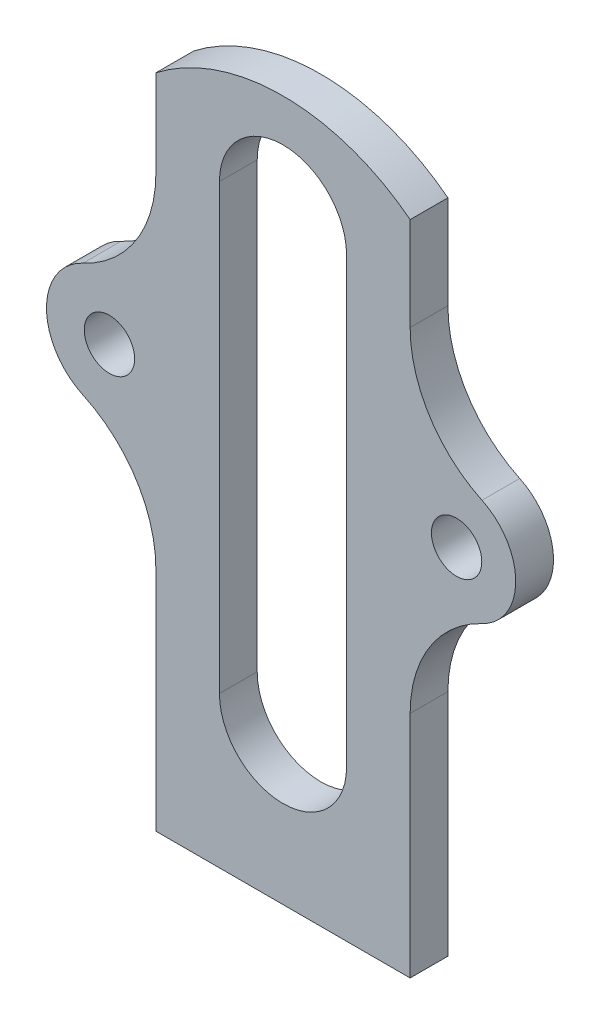
SolidWorks part; units mm, degrees
ref_plane "Front Plane" through (0, 0, 0) normal (0, 0, 1) x (1, 0, 0)
ref_plane "Top Plane" through (0, 0, 0) normal (0, 1, 0) x (1, 0, 0)
ref_plane "Right Plane" through (0, 0, 0) normal (1, 0, 0) x (0, 0, -1)
ref_plane "Plane1" through (0, 0, 26) normal (0, 0, 1) x (1, 0, 0)
sketch "Sketch1" plane through (0, 0, 26) normal (0, 0, 1) x (1, 0, 0)
  line L0 (15.15, 12) -> (15.15, 47.2223) construction
  line L1 (5.05, 47.2223) -> (5.05, 12) construction
  line L2 (15.15, 12) -> (15.15, 47.2223)
  line L3 (0, 0) -> (20.2, 0)
  line L4 (20.2, 0) -> (20.2, 52.1796)
  line L5 (0, 52.1796) -> (0, 0)
  line L6 (0, 0) -> (20.2, 0)
  line L7 (20.2, 0) -> (20.2, 18.2068)
  line L8 (0, 52.1796) -> (0, 45.2584)
  line L9 (5.05, 47.2223) -> (5.05, 12)
  line L10 (0, 18.042) -> (0, 0)
  line L11 (20.2, 44.7544) -> (20.2, 52.1796)
  line L15 (0, 52.1796) -> (0, 0) construction
  line L17 (20.2, 0) -> (20.2, 52.1796) construction
  arc A0 (5.05, 12) -> (15.15, 12) centre (10.1, 12) ccw construction
  arc A1 (20.2, 52.1796) -> (0, 52.1796) centre (10.1, 39.1851) ccw
  arc A4 (20.2, 52.1796) -> (0, 52.1796) centre (10.1, 39.1851) ccw
  arc A5 (15.15, 47.2223) -> (5.05, 47.2223) centre (10.1, 47.2223) ccw construction
  arc A6 (5.05, 12) -> (15.15, 12) centre (10.1, 12) ccw
  arc A7 (15.15, 47.2223) -> (5.05, 47.2223) centre (10.1, 47.2223) ccw
  circle A8 centre (-3.69, 31.6502) radius 2
  arc A9 (-5.7933, 36.1863) -> (-5.7933, 27.1141) centre (-3.69, 31.6502) ccw
  circle A10 centre (23.89, 31.4806) radius 2
  arc A11 (25.9067, 27.2382) -> (25.9067, 35.723) centre (23.89, 31.4806) ccw
  arc A12 (0, 18.042) -> (-5.7933, 27.1141) centre (-10, 18.042) ccw
  arc A13 (0, 45.2584) -> (-5.7933, 36.1863) centre (-10, 45.2584) cw
  arc A14 (20.2, 44.7544) -> (25.9067, 35.723) centre (30.2, 44.7544) ccw
  arc A15 (20.2, 18.2068) -> (25.9067, 27.2382) centre (30.2, 18.2068) cw
  point P33 (20.2, 34.3872)
  dimension "D2" = 4
  dimension "D3" = 10
  dimension "D4" = 10
  dimension "D5" = 4
  dimension "D6" = 10
  dimension "D7" = 10
  dimension "D8" = 10
  dimension "D10" = 4.6973
  dimension "D15" = 3.69
  dimension "D11" = 31.4806
  dimension "D12" = 31.8646
  dimension "D13" = 3.69
  dimension "D14" = 31.4806
  dimension "D1" = 0
extrude "Boss-Extrude1" add sketch "Sketch1" against normal blind 3
